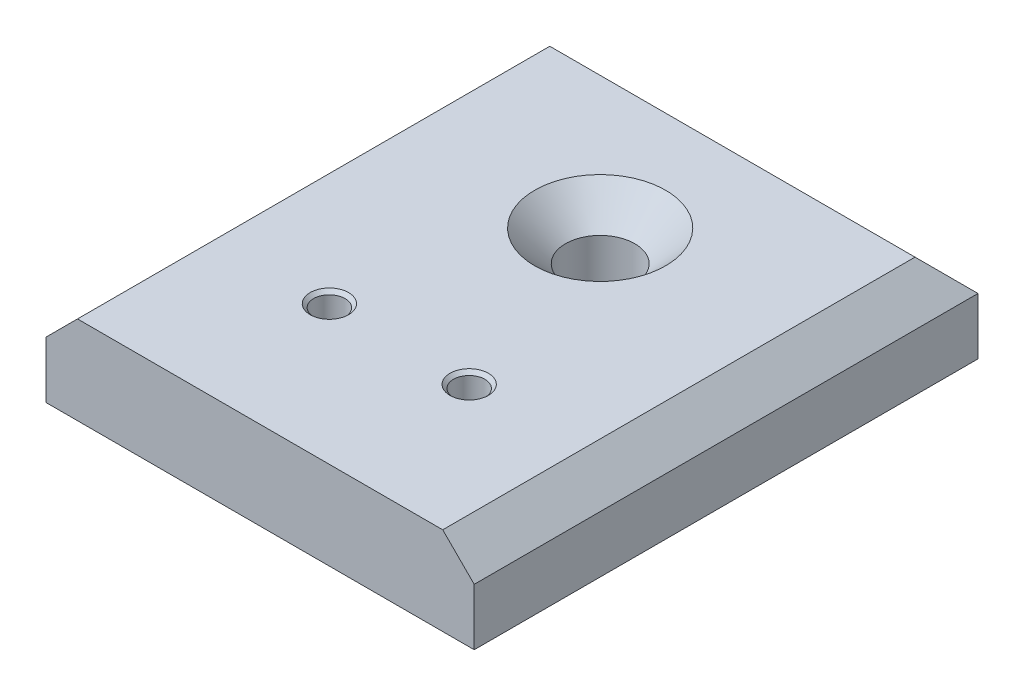
SolidWorks part; units mm, degrees
material "3.1355 (EN-AW 2024)"
ref_plane "Front" through (0, 0, 0) normal (0, 0, 1) x (1, 0, 0)
ref_plane "Top" through (0, 0, 0) normal (0, 1, 0) x (1, 0, 0)
ref_plane "Right" through (0, 0, 0) normal (1, 0, 0) x (0, 0, -1)
sketch "Эскиз1" plane through (0, 0, 0) normal (0, 1, 0) x (1, 0, 0)
  line L1 (-17, 20) -> (17, 20)
  line L2 (-17, 20) -> (-17, -20)
  line L3 (-17, -20) -> (17, -20)
  line L4 (17, 20) -> (17, -20)
  line L5 (-17, 20) -> (17, -20) construction
  line L6 (-17, -20) -> (17, 20) construction
  point P0 (0, 0)
  dimension "D1" = 40
  dimension "D2" = 34
extrude "База" add sketch "Эскиз1" along normal blind 7
hole_wizard "Крепление к профилю 40 - M5" positions "Эскиз2" profile "Эскиз3" countersink size "M5" standard "DIN" end condition through all
sketch "Эскиз2" plane through (0, 7, 0) normal (0, 1, 0) x (-1, 0, 0)
  line L0 (-17, -20) -> (17, -20) construction
  point P0 (0, -7)
  dimension "D1" = 13
sketch "Эскиз3" plane through (0, 7, -7) normal (1, 0, 0) x (0, 0, 1)
  line L0 (0, 0) -> (0, 7)
  line L1 (0, 7) -> (2.75, 7)
  line L2 (2.75, 7) -> (2.75, 2.45)
  line L3 (2.75, 2.45) -> (5.2, 0)
  line L5 (5.2, 0) -> (0, 0)
  line L6 (-2.75, 2.45) -> (-5.2, 0) construction
  line L11 (0, -6.35) -> (0, 107.95) construction
  dimension "Диаметр сквозного отверстия" = 5.5
  dimension "Глубина сквозного отверстия" = 7
  dimension "Диаметр передней зенковки" = 10.4
  dimension "Угол передней зенковки" = 90
hole_wizard "Крепление датчика" positions "Эскиз6" profile "Эскиз5" tap size "M3" standard "DIN" end condition through all
sketch "Эскиз6" plane through (0, 7, 0) normal (0, 1, 0) x (-1, 0, 0)
  line L0 (5.55, 8.95) -> (0, 8.95) construction
  line L1 (0, 8.95) -> (-5.55, 8.95) construction
  point P0 (5.55, 8.95)
  point P3 (-5.55, 8.95)
  dimension "D1" = 11.1
  dimension "D2" = 8.95
sketch "Эскиз5" plane through (-5.55, 7, 8.95) normal (1, 0, 0) x (0, 0, 1)
  line L0 (0, 0) -> (0, 7)
  line L1 (0, 7) -> (1.25, 7)
  line L2 (1.25, 7) -> (1.25, 0.275)
  line L3 (1.25, 0.275) -> (1.525, 0)
  line L5 (1.525, 0) -> (0, 0)
  line L6 (-1.25, 0.275) -> (-1.525, 0) construction
  line L11 (0, -6.35) -> (0, 107.95) construction
  dimension "Диаметр проходного сверла" = 2.5
  dimension "Глубина проходного сверла" = 7
  dimension "Диаметр передней зенковки" = 3.05
  dimension "Угол передней зенковки" = 90
cosmetic thread "Отверстие резьбы1" parameters "D2"=3
cosmetic thread "Отверстие резьбы2" parameters "D2"=3
chamfer "Фаска1" distance 2.5 angle 45 4 edges at (0, 7, 20) (17, 7, 0) (0, 7, -20) (-17, 7, 0)
